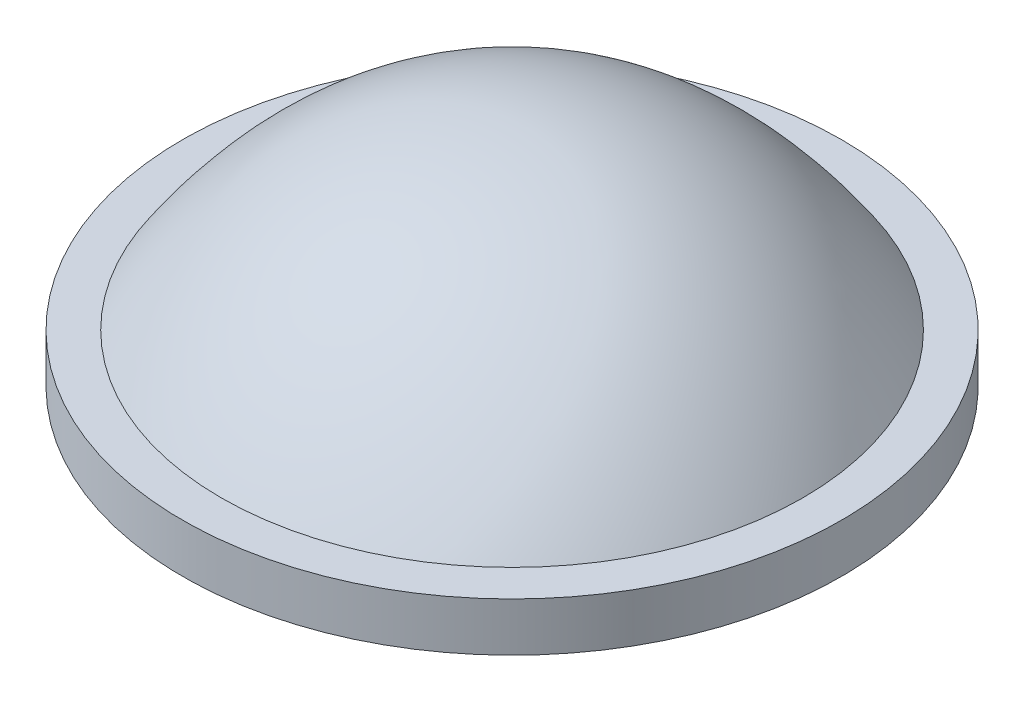
SolidWorks part; units mm, degrees
ref_plane "Front Plane" through (0, 0, 0) normal (0, 0, 1) x (1, 0, 0)
ref_plane "Top Plane" through (0, 0, 0) normal (0, 1, 0) x (1, 0, 0)
ref_plane "Right Plane" through (0, 0, 0) normal (1, 0, 0) x (0, 0, -1)
sketch "Sketch1" plane through (0, 0, 0) normal (1, 0, 0) x (0, 0, -1)
  line L0 (0, 0) -> (0, 16.6354) construction
  line L1 (0, 0) -> (0, 7.8)
  line L2 (0, 0) -> (-11.5, 0)
  line L3 (-11.5, 0) -> (-11.5, 1.7)
  line L4 (-11.5, 1.7) -> (-10.15, 1.7)
  line L5 (6.3547, 7.8) -> (-6.3547, 7.8) construction
  spline S0 degree 2 poles (-10.15, 1.7) (-6.0813, 7.8) (0, 7.8) knots 0 0 0 1 1 1
  dimension "D1" = 7.8
  dimension "D2" = 1.7
  dimension "D3" = 11.5
  dimension "D4" = 10.15
revolve "Revolve1" add sketch "Sketch1" angle 360 about L0
equation "\"D4@Sketch1\"=20.3/2"
